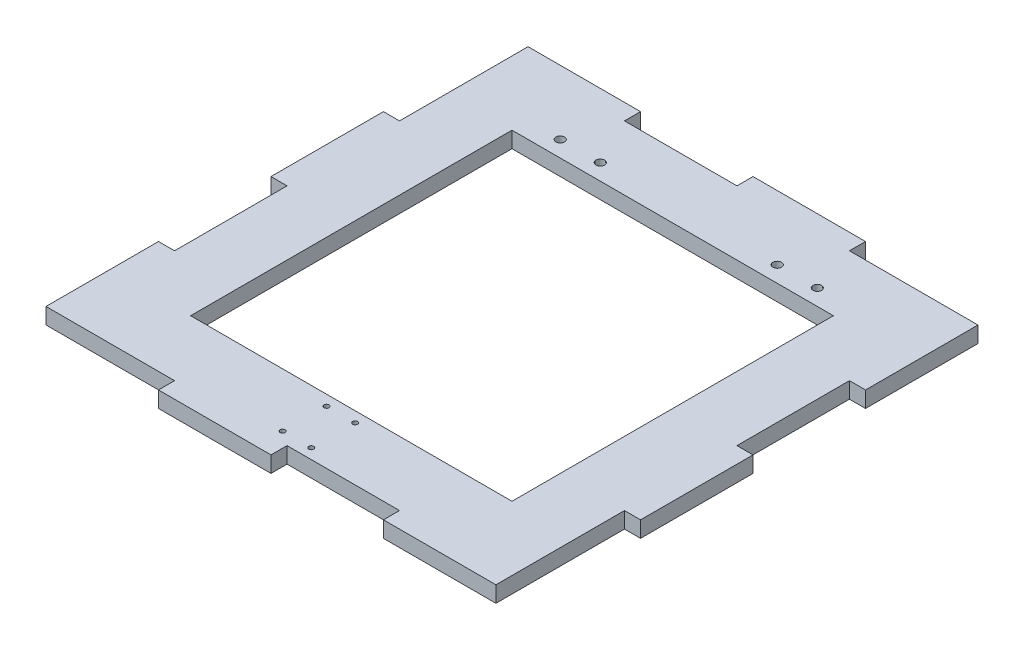
SolidWorks part; units mm, degrees
material "Acrylic (Medium-high impact)"
ref_plane "Front Plane" through (0, 0, 0) normal (0, 0, 1) x (1, 0, 0)
ref_plane "Top Plane" through (0, 0, 0) normal (0, 1, 0) x (1, 0, 0)
ref_plane "Right Plane" through (0, 0, 0) normal (1, 0, 0) x (0, 0, -1)
sketch "Sketch1" plane through (0, 0, 0) normal (0, 1, 0) x (1, 0, 0)
  line L0 (-148.9886, 47.954) -> (-155.3386, 47.954)
  line L1 (-148.9886, 92.404) -> (28.8114, 92.404)
  line L2 (-148.9886, 92.404) -> (-148.9886, -85.396)
  line L3 (-148.9886, -85.396) -> (28.8114, -85.396)
  line L4 (28.8114, 92.404) -> (28.8114, -85.396)
  line L5 (-155.3386, 47.954) -> (-155.3386, 3.504)
  line L6 (-155.3386, 3.504) -> (-148.9886, 3.504)
  line L7 (-148.9886, 3.504) -> (-148.9886, -40.946)
  line L8 (-148.9886, -40.946) -> (-155.3386, -40.946)
  line L9 (-155.3386, -40.946) -> (-155.3386, -85.396)
  line L10 (-155.3386, -85.396) -> (-148.9886, -85.396)
  line L11 (-15.6386, 92.404) -> (-15.6386, 98.754)
  line L12 (-15.6386, 98.754) -> (-60.0886, 98.754)
  line L13 (-60.0886, 98.754) -> (-60.0886, 92.404)
  line L14 (-104.5386, 92.404) -> (-104.5386, 98.754)
  line L15 (-104.5386, 98.754) -> (-148.9886, 98.754)
  line L16 (-148.9886, 98.754) -> (-148.9886, 92.404)
  line L17 (3.4114, -59.996) -> (-123.5886, -59.996)
  line L18 (3.4114, -59.996) -> (3.4114, 67.004)
  line L19 (3.4114, 67.004) -> (-123.5886, 67.004)
  line L20 (-123.5886, -59.996) -> (-123.5886, 67.004)
  line L21 (28.8114, -40.946) -> (35.1614, -40.946)
  line L22 (35.1614, -40.946) -> (35.1614, 3.504)
  line L23 (35.1614, 3.504) -> (28.8114, 3.504)
  line L24 (28.8114, 47.954) -> (35.1614, 47.954)
  line L25 (35.1614, 47.954) -> (35.1614, 92.404)
  line L26 (35.1614, 92.404) -> (28.8114, 92.404)
  line L27 (-104.5386, -85.396) -> (-104.5386, -91.746)
  line L28 (-104.5386, -91.746) -> (-60.0886, -91.746)
  line L29 (-60.0886, -91.746) -> (-60.0886, -85.396)
  line L30 (-15.6386, -85.396) -> (-15.6386, -91.746)
  line L31 (-15.6386, -91.746) -> (28.8114, -91.746)
  line L32 (28.8114, -91.746) -> (28.8114, -85.396)
  circle A2 centre (-9.2886, 73.354) radius 1.7018
  circle A3 centre (-25.1255, 73.354) radius 1.7018
  circle A4 centre (-95.0517, 73.354) radius 1.7018
  circle A5 centre (-110.8886, 73.354) radius 1.7018
  circle A6 centre (-65.7464, -64.1241) radius 0.9842
  circle A7 centre (-54.4307, -64.1241) radius 0.9842
  circle A8 centre (-54.5736, -81.332) radius 0.9842
  circle A9 centre (-65.8893, -81.332) radius 0.9842
  point P4 (-60.0886, 92.404)
  point P5 (-148.9886, 3.504)
  point P6 (-148.9886, 47.954)
  point P7 (-148.9886, 3.504)
  point P8 (-148.9886, -40.946)
  point P9 (28.8114, 3.504)
  point P10 (-60.0886, -85.396)
  point P14 (-60.0886, 3.504)
  point P50 (-60.0886, 3.9583)
  point P64 (-60.0886, -64.1241)
  point P65 (-22.5197, -59.996)
  point P66 (-60.0886, -64.1241)
  point P67 (-16.9078, -96.5693)
  point P68 (-60.0886, -64.1241)
  point P74 (-60.0886, 3.504)
  dimension "D13" = 3.4036
  dimension "D15" = 3.4036
  dimension "D16" = 3.4036
  dimension "D14" = 3.4036
  dimension "D25" = 1.9685
  dimension "D26" = 1.9685
  dimension "D27" = 1.9685
  dimension "D28" = 1.9685
  dimension "D1" = 177.8
  dimension "D2" = 177.8
  dimension "D3" = 44.45
  dimension "D4" = 44.45
  dimension "D5" = 44.45
  dimension "D6" = 6.35
  dimension "D7" = 127
  dimension "D8" = 127
  dimension "D9" = 25.4
  dimension "D10" = 25.4
  dimension "D11" = 6.35
  dimension "D17" = 6.35
  dimension "D18" = 6.35
  dimension "D19" = 6.35
  dimension "D20" = 6.35
  dimension "D21" = 15.8369
  dimension "D22" = 15.8369
  dimension "D23" = 12.7
  dimension "D24" = 12.7
  dimension "D29" = 17.2085
  dimension "D30" = 17.2085
  dimension "D31" = 4.064
  dimension "D32" = 4.064
  dimension "D33" = 11.3157
  dimension "D34" = 5.6578
  dimension "D35" = 11.3157
  dimension "D36" = 20.5169
  dimension "D37" = 5.6579
  dimension "D38" = 88.9
  dimension "D39" = 88.9
  dimension "D40" = 0
  dimension "D41" = 88.9
extrude "Boss-Extrude1" add sketch "Sketch1" along normal blind 6.35
